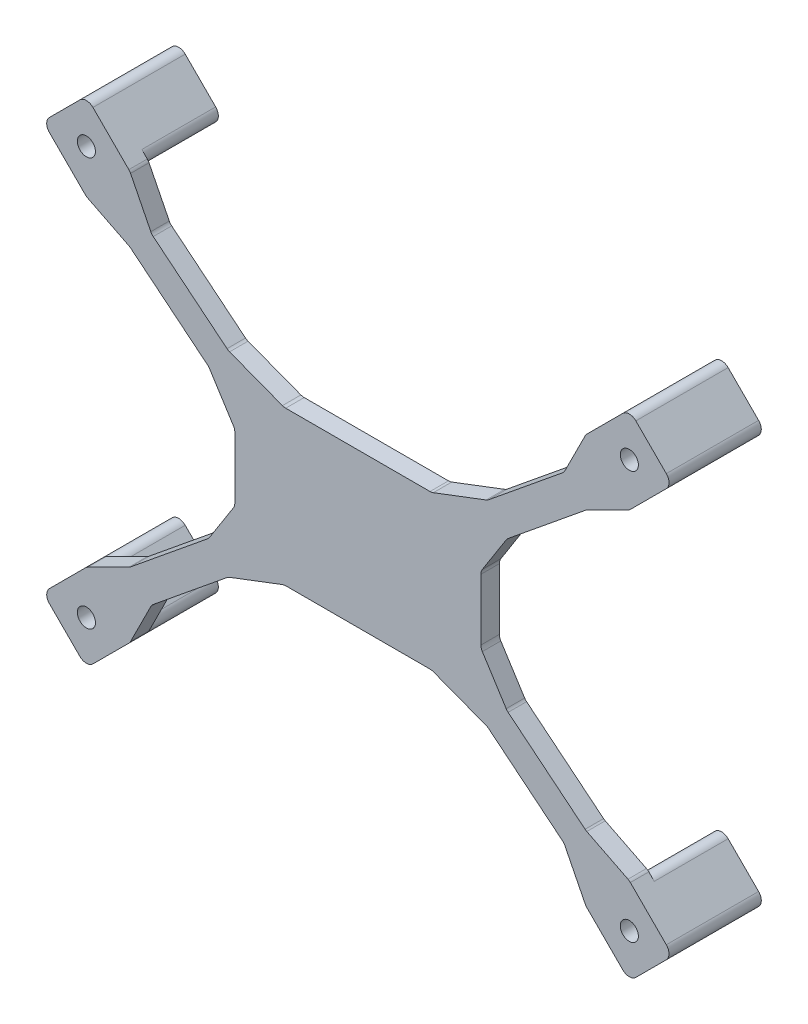
SolidWorks part; units mm, degrees
ref_plane "Front Plane" through (0, 0, 0) normal (0, 0, 1) x (1, 0, 0)
ref_plane "Top Plane" through (0, 0, 0) normal (0, 1, 0) x (1, 0, 0)
ref_plane "Right Plane" through (0, 0, 0) normal (1, 0, 0) x (0, 0, -1)
sketch "Sketch1" plane through (0, 0, 0) normal (0, 0, 1) x (1, 0, 0)
  line L0 (-44.125, -33.16) -> (-44.125, 33.16) construction
  line L1 (44.125, 33.16) -> (44.125, -33.16) construction
  line L2 (-44.125, 0) -> (44.125, 0) construction
  line L3 (-51.1961, 33.16) -> (-44.125, 40.2311)
  line L4 (-51.1961, 33.16) -> (-44.125, 26.0889)
  line L5 (-44.125, 40.2311) -> (-37.0539, 33.16)
  line L6 (-44.125, 26.0889) -> (-37.0539, 33.16)
  line L7 (-51.1961, 33.16) -> (-37.0539, 33.16) construction
  line L8 (-44.125, 40.2311) -> (-44.125, 26.0889) construction
  line L9 (44.125, 26.0889) -> (37.0539, 33.16)
  line L10 (44.125, 26.0889) -> (51.1961, 33.16)
  line L11 (37.0539, 33.16) -> (44.125, 40.2311)
  line L12 (51.1961, 33.16) -> (44.125, 40.2311)
  line L13 (44.125, 26.0889) -> (44.125, 40.2311) construction
  line L14 (37.0539, 33.16) -> (51.1961, 33.16) construction
  line L15 (37.0539, -33.16) -> (44.125, -26.0889)
  line L16 (37.0539, -33.16) -> (44.125, -40.2311)
  line L17 (44.125, -26.0889) -> (51.1961, -33.16)
  line L18 (44.125, -40.2311) -> (51.1961, -33.16)
  line L19 (37.0539, -33.16) -> (51.1961, -33.16) construction
  line L20 (44.125, -26.0889) -> (44.125, -40.2311) construction
  line L21 (-44.125, -40.2311) -> (-51.1961, -33.16)
  line L22 (-44.125, -40.2311) -> (-37.0539, -33.16)
  line L23 (-51.1961, -33.16) -> (-44.125, -26.0889)
  line L24 (-37.0539, -33.16) -> (-44.125, -26.0889)
  line L25 (-44.125, -40.2311) -> (-44.125, -26.0889) construction
  line L26 (-51.1961, -33.16) -> (-37.0539, -33.16) construction
  point P2 (-44.125, 0)
  point P4 (44.125, 0)
  point P7 (0, 0)
  point P10 (-46.2492, 39.7503)
  point P11 (-45.0931, 40.4063)
  point P12 (-43.2259, -26.1463)
  point P29 (-44.125, -26.1463)
  point P30 (-44.125, 26.0889)
  point P31 (0, 0)
  point P32 (0, 0)
  dimension "D1" = 66.32
  dimension "D2" = 88.25
  dimension "D3" = 10
extrude "Boss-Extrude1" add sketch "Sketch1" along normal blind 15
sketch "Sketch2" plane through (0, 0, 15) normal (0, 0, 1) x (1, 0, 0)
  line L0 (-44.125, 26.0889) -> (-37.063, 22.5443)
  line L1 (-37.063, 22.5443) -> (-20, 8.6256)
  line L2 (-20, 8.6256) -> (-20, -8.6256)
  line L3 (0, 0) -> (-20, 0) construction
  line L4 (-44.125, -26.0889) -> (-37.063, -22.5443)
  line L5 (-37.063, -22.5443) -> (-20, -8.6256)
  line L6 (-44.125, 26.0889) -> (-37.0539, 33.16) construction
  line L7 (-24.2395, 12.0839) -> (-20, 5.4159)
  line L8 (-20, 5.4159) -> (-18.4279, 7.3431) construction
  line L9 (-18.4279, 7.3431) -> (-20, 8.6256) construction
  line L10 (0, 0) -> (0, 12.5) construction
  line L11 (-37.063, 22.5443) -> (-33.5093, 26.098) construction
  line L12 (-33.5093, 26.098) -> (-16.8395, 12.5)
  line L13 (-37.0539, 33.16) -> (-33.5093, 26.098)
  line L14 (-33.5093, -26.098) -> (-16.8395, -12.5)
  line L15 (-37.0539, -33.16) -> (-33.5093, -26.098)
  line L16 (-16.8395, 12.5) -> (16.8395, 12.5)
  line L17 (-16.8395, -12.5) -> (16.8395, -12.5)
  line L18 (-37.0539, -33.16) -> (-44.125, -26.0889) construction
  line L19 (-37.0539, -33.16) -> (-44.125, -26.0889)
  line L20 (-44.125, 26.0889) -> (-37.0539, 33.16)
  line L21 (33.5093, -26.098) -> (16.8395, -12.5)
  line L22 (37.0539, -33.16) -> (33.5093, -26.098)
  line L23 (37.0539, -33.16) -> (44.125, -26.0889)
  line L24 (44.125, -26.0889) -> (37.063, -22.5443)
  line L25 (37.063, -22.5443) -> (20, -8.6256)
  line L26 (20, 8.6256) -> (20, -8.6256)
  line L27 (37.063, 22.5443) -> (20, 8.6256)
  line L28 (44.125, 26.0889) -> (37.063, 22.5443)
  line L29 (33.5093, 26.098) -> (16.8395, 12.5)
  line L30 (37.0539, 33.16) -> (33.5093, 26.098)
  line L31 (44.125, 26.0889) -> (37.0539, 33.16)
  line L32 (-16.8395, 12.5) -> (-20, 8.6256)
  line L33 (-21.079, 15.9583) -> (-13.6953, 13.1448)
  line L34 (-18.4198, 10.5628) -> (-35.2862, 24.3212) construction
  line L35 (-13.6953, 13.1448) -> (-12.0029, 12.5)
  line L36 (-24.2395, -12.0839) -> (-20, -5.4159)
  line L37 (-21.079, -15.9583) -> (-13.6953, -13.1448)
  line L38 (-13.6953, -13.1448) -> (-12.0029, -12.5)
  line L39 (24.2395, -12.0839) -> (20, -5.4159)
  line L40 (21.079, -15.9583) -> (13.6953, -13.1448)
  line L41 (13.6953, -13.1448) -> (12.0029, -12.5)
  line L42 (24.2395, 12.0839) -> (20, 5.4159)
  line L43 (21.079, 15.9583) -> (13.6953, 13.1448)
  line L44 (13.6953, 13.1448) -> (12.0029, 12.5)
  line M41 (-44.125, 26.0889) -> (-37.0539, 33.16)
  dimension "D1" = 7.5
  dimension "D2" = 25
  dimension "D3" = 5
  dimension "D4" = 40
  dimension "D5" = 7.5
extrude "Boss-Extrude2" add sketch "Sketch2" against normal blind 3 contours L16 L32 L2 L5 L4 L19 L15 L14 L17 L21 L22 L23 L24 L25 L26 L27 L28 L31 L30 L29 | L35 L33 L12 L16 | L32 L12 L13 L0 L1 M41 | L1 L7 L2 | L36 L5 L2 | L37 L38 L17 L14 | L41 L40 L21 L17 | L25 L39 L26 | L42 L27 L26 | L43 L44 L16 L29
hole_wizard "#2 Clearance Hole1" positions "Sketch5" profile "Sketch4" hole size "#2" standard "ANSI Inch" end condition through all
sketch "Sketch5" plane through (0, 0, 0) normal (0, 0, -1) x (-1, 0, 0)
  line L0 (44.125, -40.2311) -> (44.125, -26.0889) construction
  line L1 (-44.125, -26.0889) -> (-44.125, -40.2311) construction
  point P0 (-44.125, 33.16)
  point P3 (44.125, 33.16)
  point P6 (44.125, -33.16)
  point P10 (-44.125, -33.16)
sketch "Sketch4" plane through (44.125, 33.16, 0) normal (1, 0, 0) x (0, 1, 0)
  line L0 (0, 0) -> (0, 15)
  line L1 (0, 15) -> (1.4732, 15)
  line L2 (1.4732, 15) -> (1.4732, 0)
  line L5 (1.4732, 0) -> (0, 0)
  line L11 (0, -6.35) -> (0, 107.95) construction
  dimension "Thru Hole Dia." = 2.9464
  dimension "Thru Hole Depth" = 15
fillet "Fillet2" radius 1.5 16 edges at (-37.0539, -33.16, 6) (-44.125, -26.0889, 6) (-51.1961, -33.16, 7.5) (-44.125, -40.2311, 7.5) (44.125, -40.2311, 7.5) (44.125, -26.0889, 6) (37.0539, -33.16, 6) (51.1961, -33.16, 7.5) (44.125, 40.2311, 7.5) (37.0539, 33.16, 6) (44.125, 26.0889, 6) (51.1961, 33.16, 7.5) (-44.125, 26.0889, 6) (-37.0539, 33.16, 6) (-51.1961, 33.16, 7.5) (-44.125, 40.2311, 7.5)
fillet "Fillet3" radius 1.5 32 edges at (-44.125, -26.0889, 13.5) (-37.063, -22.5443, 13.5) (-24.2395, -12.0839, 13.5) (-20, -5.4159, 13.5) (-20, 5.4159, 13.5) (-24.2395, 12.0839, 13.5) (-37.063, 22.5443, 13.5) (-44.125, 26.0889, 13.5) (-37.0539, 33.16, 13.5) (-33.5093, 26.098, 13.5) (-21.079, 15.9583, 13.5) (-12.0029, 12.5, 13.5) (12.0029, 12.5, 13.5) (21.079, 15.9583, 13.5) (33.5093, 26.098, 13.5) (37.0539, 33.16, 13.5) (44.125, 26.0889, 13.5) (37.063, 22.5443, 13.5) (24.2395, 12.0839, 13.5) (20, 5.4159, 13.5) (20, -5.4159, 13.5) (24.2395, -12.0839, 13.5) (37.063, -22.5443, 13.5) (44.125, -26.0889, 13.5) (37.0539, -33.16, 13.5) (33.5093, -26.098, 13.5) (21.079, -15.9583, 13.5) (12.0029, -12.5, 13.5) (-12.0029, -12.5, 13.5) (-21.079, -15.9583, 13.5) (-33.5093, -26.098, 13.5) (-37.0539, -33.16, 13.5)
